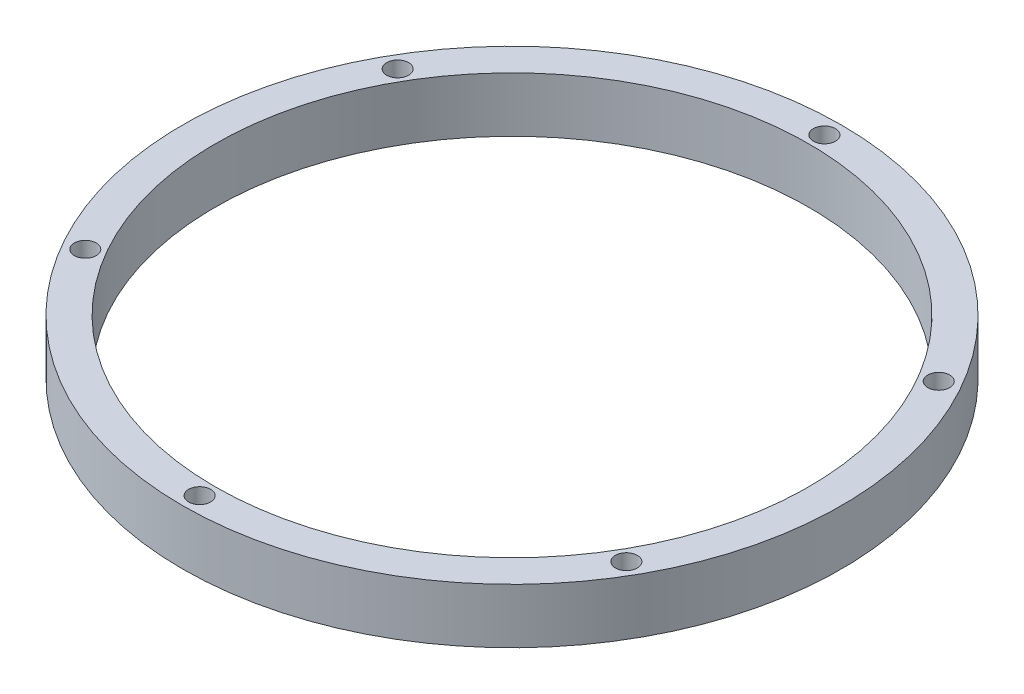
SolidWorks part; units mm, degrees
ref_plane "前视基准面" through (0, 0, 0) normal (0, 0, 1) x (1, 0, 0)
ref_plane "上视基准面" through (0, 0, 0) normal (0, 1, 0) x (1, 0, 0)
ref_plane "右视基准面" through (0, 0, 0) normal (1, 0, 0) x (0, 0, -1)
other "Configuration Table"
sketch "草图1" plane through (0, 0, 0) normal (0, 1, 0) x (1, 0, 0)
  line L0 (0, 48) -> (0, 43.25) construction
  circle A0 centre (0, 0) radius 43.25
  circle A1 centre (0, 0) radius 48
  circle A2 centre (0, 45.5) radius 1.6
  circle A3 centre (39.4042, 22.75) radius 1.6
  circle A4 centre (39.4042, -22.75) radius 1.6
  circle A5 centre (0, -45.5) radius 1.6
  circle A6 centre (-39.4042, -22.75) radius 1.6
  circle A7 centre (-39.4042, 22.75) radius 1.6
  point P20 (0, 0)
  dimension "D1" = 86.5
  dimension "D2" = 96
  dimension "D3" = 3.2
  dimension "D5" = 2.5
  dimension "D4" = 6
extrude "凸台-拉伸1" add sketch "草图1" along normal blind 8
